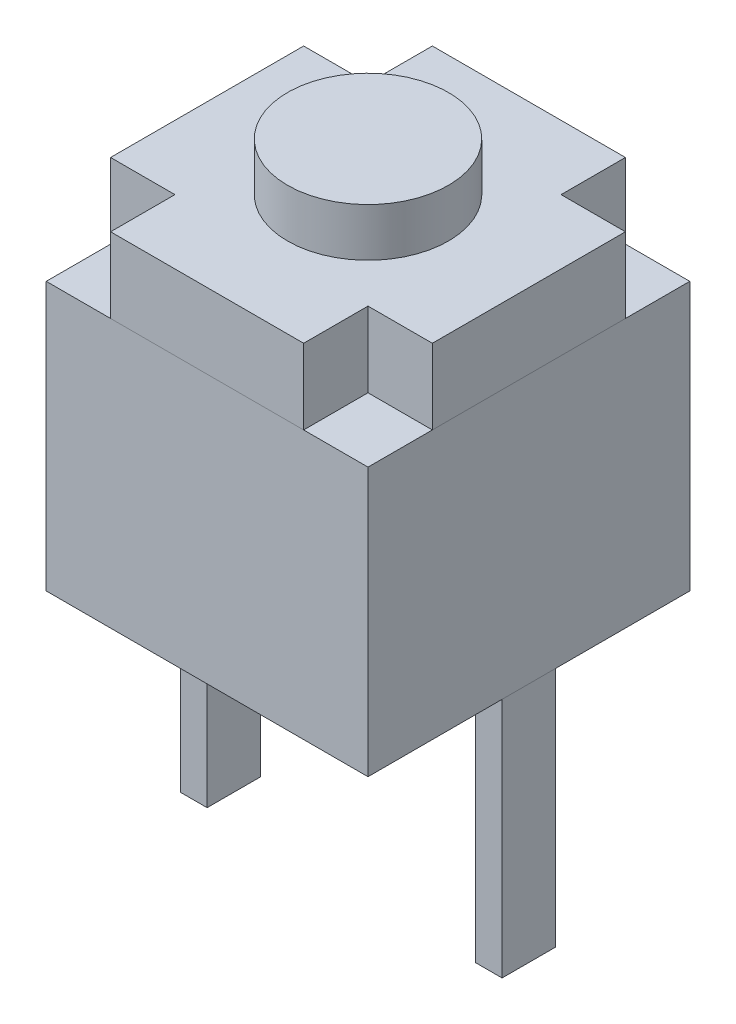
SolidWorks part; units mm, degrees
ref_plane "前视基准面" through (0, 0, 0) normal (0, 0, 1) x (1, 0, 0)
ref_plane "上视基准面" through (0, 0, 0) normal (0, 1, 0) x (1, 0, 0)
ref_plane "右视基准面" through (0, 0, 0) normal (1, 0, 0) x (0, 0, -1)
sketch "草图1" plane through (0, 0, 0) normal (0, 1, 0) x (1, 0, 0)
  line L1 (-3, -3) -> (3, -3)
  line L2 (-3, -3) -> (-3, 3)
  line L3 (-3, 3) -> (3, 3)
  line L4 (3, -3) -> (3, 3)
  line L5 (-3, -3) -> (3, 3) construction
  line L6 (-3, 3) -> (3, -3) construction
  point P0 (0, 0)
  dimension "D1" = 6
  dimension "D2" = 6
extrude "凸台-拉伸1" add sketch "草图1" along normal blind 5
sketch "草图3" plane through (0, 5, 0) normal (0, 1, 0) x (1, 0, 0)
  line L1 (3, 3) -> (1.8, 3)
  line L2 (3, 3) -> (3, 1.8)
  line L3 (3, 1.8) -> (1.8, 1.8)
  line L4 (3, -3) -> (3, 3)
  line L5 (3, 3) -> (-3, 3)
  line L6 (-3, 3) -> (-3, -3)
  line L7 (-3, -3) -> (3, -3)
  line L8 (3, -3) -> (3, 3)
  line L9 (3, 3) -> (-3, 3)
  line L10 (-3, 3) -> (-3, -3)
  line L11 (-3, -3) -> (3, -3)
  line L12 (1.8, 3) -> (1.8, 1.8)
  line L13 (3, -3) -> (1.8, -3)
  line L14 (3, -3) -> (3, -1.8)
  line L15 (3, -1.8) -> (1.8, -1.8)
  line L16 (1.8, -3) -> (1.8, -1.8)
  line L17 (-3, 3) -> (-1.8, 3)
  line L18 (-3, 3) -> (-3, 1.8)
  line L19 (-3, 1.8) -> (-1.8, 1.8)
  line L20 (-1.8, 3) -> (-1.8, 1.8)
  line L21 (-3, -3) -> (-1.8, -3)
  line L22 (-3, -3) -> (-3, -1.8)
  line L23 (-3, -1.8) -> (-1.8, -1.8)
  line L24 (-1.8, -3) -> (-1.8, -1.8)
  line M7 (3, 3) -> (-3, 3)
  dimension "D2" = 1.2
  dimension "D1" = 0
extrude "凸台-拉伸2" add sketch "草图3" along normal blind 1.4 separate body contours L24 L11 L16 L15 L8 L3 L12 L20 L19 L10 L23 M7
sketch "草图4" plane through (0, 6.4, 0) normal (0, 1, 0) x (1, 0, 0)
  circle A0 centre (0, 0) radius 1.5
  dimension "D1" = 3
extrude "凸台-拉伸3" add sketch "草图4" along normal blind 0.9
sketch "草图5" plane through (0, 0, 0) normal (0, -1, 0) x (1, 0, 0)
  line L0 (0, 0) -> (3, 0) construction
  line L1 (3, 3) -> (3, -3) construction
  line L2 (0, 0) -> (0, 1.5121) construction
  line L3 (2.5, -0.5) -> (3, -0.5)
  line L4 (2.5, -0.5) -> (2.5, 0.5)
  line L5 (2.5, 0.5) -> (3, 0.5)
  line L6 (3, -0.5) -> (3, 0.5)
  line L7 (2.5, -0.5) -> (3, 0.5) construction
  line L8 (2.5, 0.5) -> (3, -0.5) construction
  line L9 (-2.5, -0.5) -> (-2.5, 0.5)
  line L10 (-2.5, -0.5) -> (-3, -0.5)
  line L11 (-3, -0.5) -> (-3, 0.5)
  line L12 (-2.5, 0.5) -> (-3, 0.5)
  point P5 (2.75, 0)
  dimension "D1" = 1
  dimension "D2" = 0.5
extrude "凸台-拉伸4" add sketch "草图5" along normal blind 4.5 separate body
